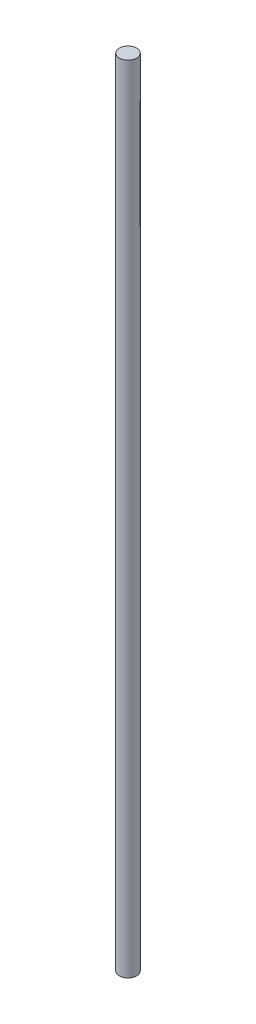
SolidWorks part; units mm, degrees
ref_plane "Front Plane" through (0, 0, 0) normal (0, 0, 1) x (1, 0, 0)
ref_plane "Top Plane" through (0, 0, 0) normal (0, 1, 0) x (1, 0, 0)
ref_plane "Right Plane" through (0, 0, 0) normal (1, 0, 0) x (0, 0, -1)
sketch "Sketch1" plane through (0, 0, 0) normal (0, 1, 0) x (1, 0, 0)
  circle A0 centre (0, 0) radius 75
  dimension "D1" = 150
extrude "Boss-Extrude2" add sketch "Sketch1" along normal blind 6875
